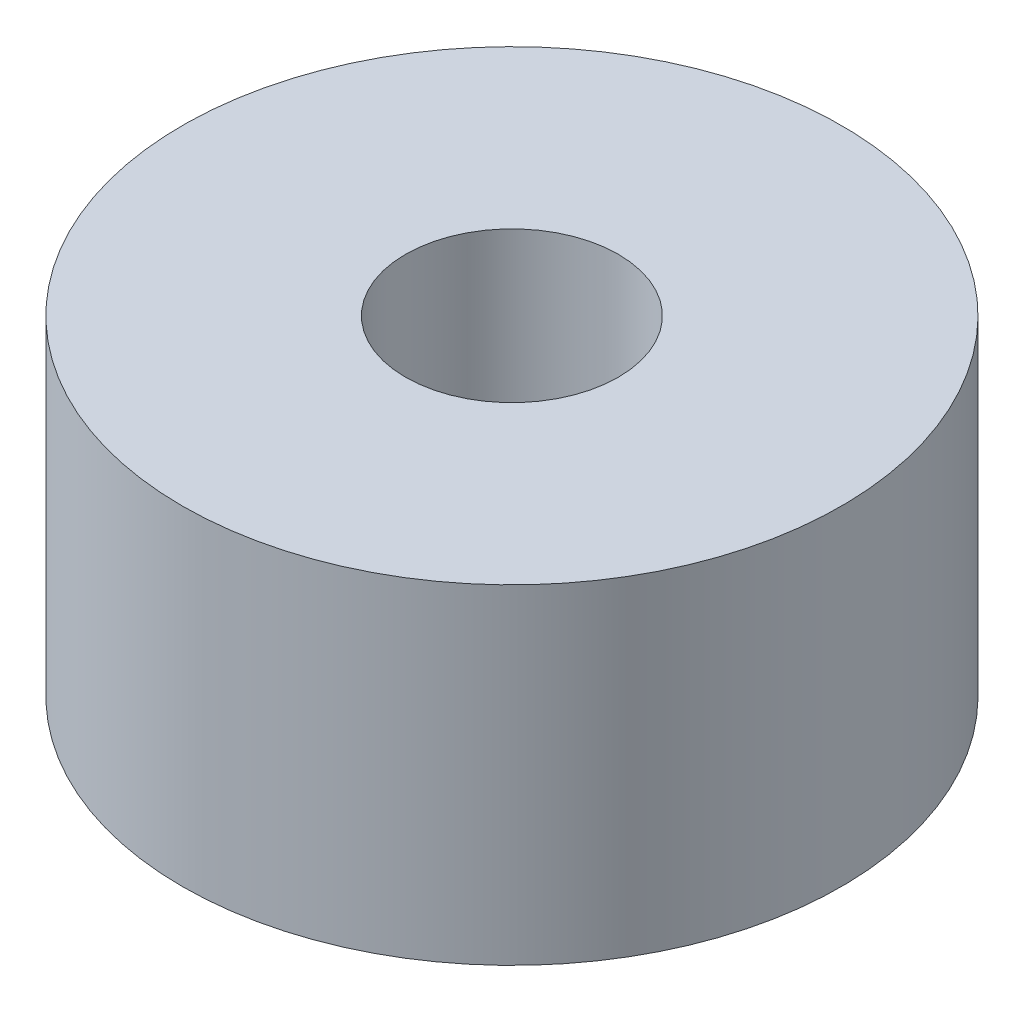
SolidWorks part; units mm, degrees
ref_plane "Front Plane" through (0, 0, 0) normal (0, 0, 1) x (1, 0, 0)
ref_plane "Top Plane" through (0, 0, 0) normal (0, 1, 0) x (1, 0, 0)
ref_plane "Right Plane" through (0, 0, 0) normal (1, 0, 0) x (0, 0, -1)
sketch "Sketch1" plane through (0, 0, 0) normal (0, 1, 0) x (1, 0, 0)
  circle A0 centre (0, 0) radius 12.7
  circle A1 centre (0, 0) radius 4.1021
  dimension "D1" = 8.2042
  dimension "D2" = 25.4
extrude "Boss-Extrude1" add sketch "Sketch1" along normal blind 12.7
